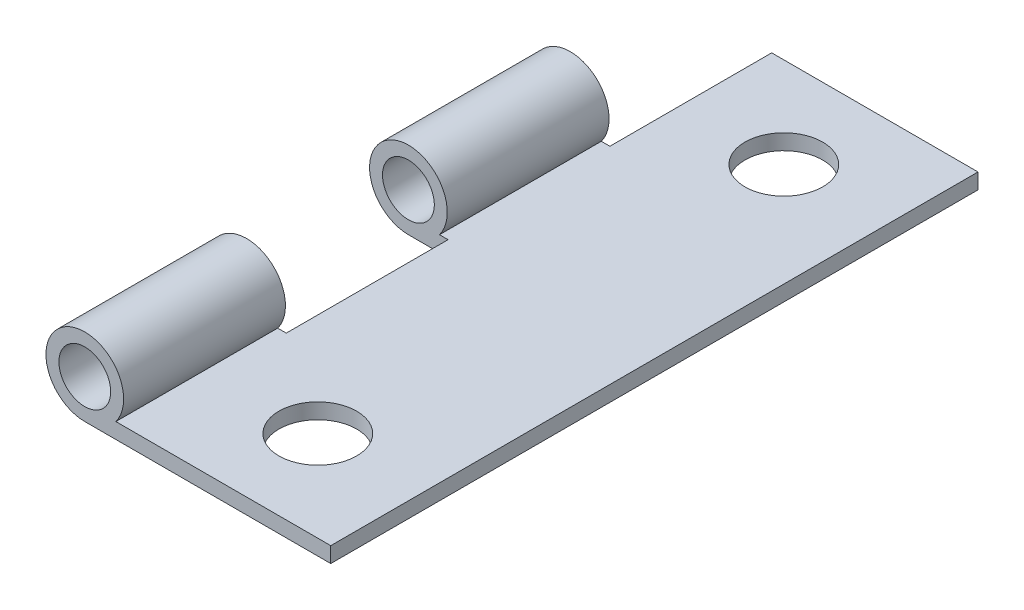
SolidWorks part; units mm, degrees
ref_plane "前视基准面" through (0, 0, 0) normal (0, 0, 1) x (1, 0, 0)
ref_plane "上视基准面" through (0, 0, 0) normal (0, 1, 0) x (1, 0, 0)
ref_plane "右视基准面" through (0, 0, 0) normal (1, 0, 0) x (0, 0, -1)
sketch "草图2" plane through (0, 0, 0) normal (0, 0, 1) x (1, 0, 0)
  line L0 (0, -1.5) -> (9.5, -1.5)
  line L5 (9.5, -1.5) -> (9.5, -0.9)
  line L6 (9.5, -0.9) -> (1.2, -0.9)
  circle A2 centre (0, 0) radius 1
  arc A3 (1.2, -0.9) -> (0, -1.5) centre (0, 0) ccw
  dimension "D1" = 2
  dimension "D2" = 3
  dimension "D3" = 9.5
  dimension "D4" = 0.6
extrude "凸台-拉伸1" add sketch "草图2" along normal mid plane 25
sketch "草图3" plane through (0, -0.9, 0) normal (0, 1, 0) x (1, 0, 0)
  line L0 (1.5, 12.5) -> (-1.5, 12.5) construction
  line L1 (-2.0085, 12.5) -> (1.5315, 12.5)
  line L2 (-2.0085, 12.5) -> (-2.0085, 6.25)
  line L3 (-2.0085, 6.25) -> (1.5315, 6.25)
  line L4 (1.5315, 12.5) -> (1.5315, 6.25)
  line L5 (-2.4653, 0) -> (1.5315, 0)
  line L6 (-2.4653, 0) -> (-2.4653, -6.25)
  line L7 (-2.4653, -6.25) -> (1.5315, -6.25)
  line L8 (1.5315, 0) -> (1.5315, -6.25)
  line L9 (-1.5, -12.5) -> (1.5, -12.5) construction
  line L10 (1.5315, 6.25) -> (1.5315, 0) construction
  dimension "D1" = 0
  dimension "D2" = 6.25
  dimension "D3" = 6.25
  dimension "D4" = 6.25
extrude "切除-拉伸1" cut sketch "草图3" against normal mid plane 25
sketch "草图4" plane through (0, -0.9, 0) normal (0, 1, 0) x (1, 0, 0)
  line L0 (9.5, 12.5) -> (1.5315, 12.5) construction
  line L1 (5.5, 9) -> (5.5, -9) construction
  circle A0 centre (5.5, 9) radius 1.5
  circle A1 centre (5.5, -9) radius 1.5
  dimension "D1" = 3
  dimension "D2" = 3
  dimension "D3" = 18
  dimension "D4" = 3.5
  dimension "D5" = 5.5
extrude "切除-拉伸2" cut sketch "草图4" against normal blind 10
